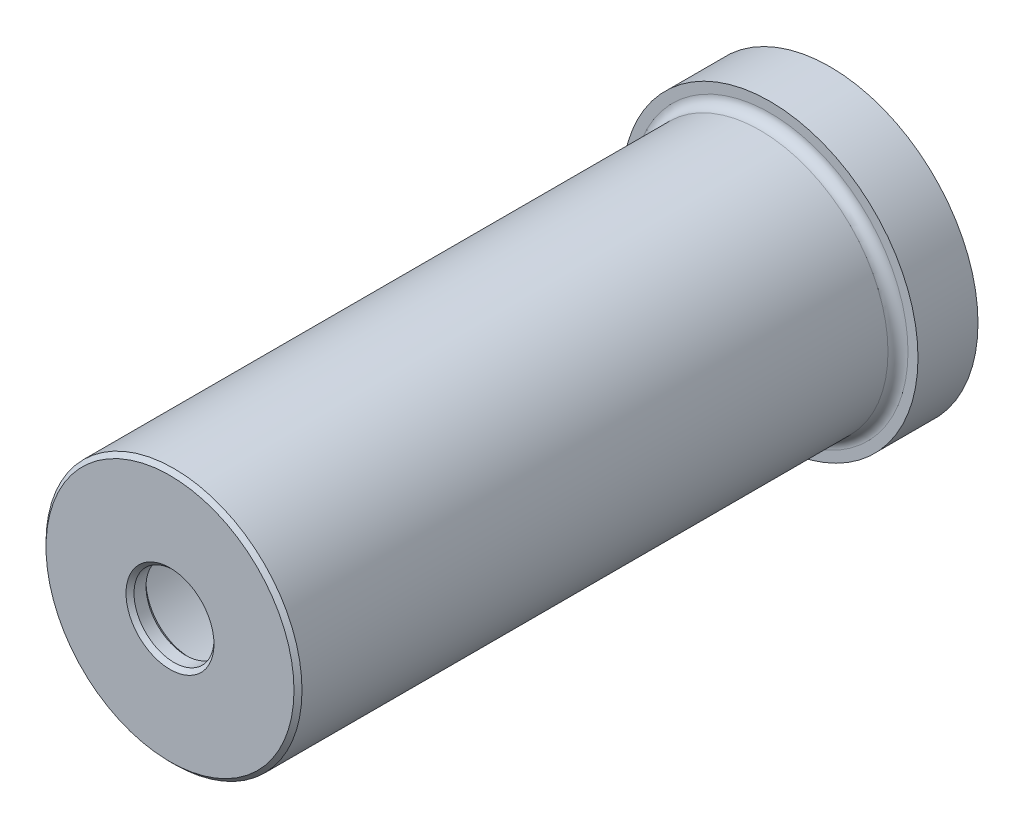
SolidWorks part; units mm, degrees
material "合金钢"
ref_plane "前视基准面" through (0, 0, 0) normal (0, 0, 1) x (1, 0, 0)
ref_plane "上视基准面" through (0, 0, 0) normal (0, 1, 0) x (1, 0, 0)
ref_plane "右视基准面" through (0, 0, 0) normal (1, 0, 0) x (0, 0, -1)
sketch "Sketch1" plane through (0, 0, 0) normal (0, 0, 1) x (1, 0, 0)
  circle A0 centre (0, 0) radius 74
  dimension "D1" = 148
extrude "Extrude1" add sketch "Sketch1" along normal blind 30
sketch "Sketch2" plane through (0, 0, 30) normal (0, 0, 1) x (1, 0, 0)
  circle A0 centre (0, 0) radius 64
  dimension "D1" = 128
extrude "Extrude2" add sketch "Sketch2" along normal blind 300
shell "Shell1" thickness 10
fillet "Fillet2" radius 5 1 edges at (64, 0, 30)
chamfer "Chamfer2" distance 2 angle 45 1 edges at (64, 0, 330)
sketch "Sketch3" plane through (0, 0, 330) normal (0, 0, 1) x (1, 0, 0)
  circle A0 centre (0, 0) radius 20
  dimension "D1" = 40
extrude "Extrude3" cut sketch "Sketch3" against normal through all
chamfer "Chamfer3" distance 2 angle 45 2 edges at (20, 0, 320) (20, 0, 330)
